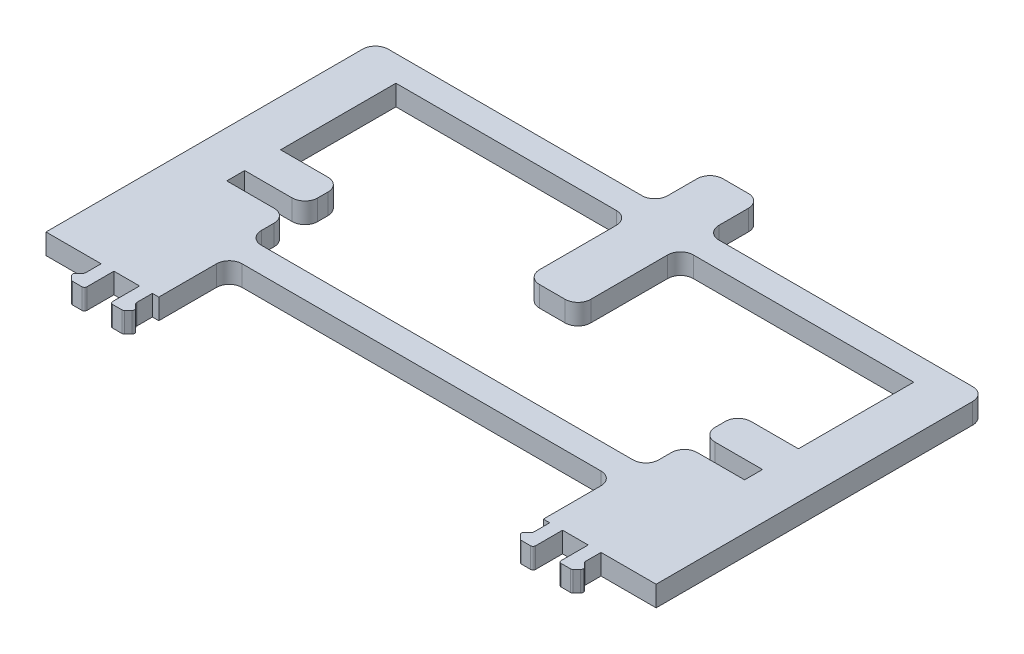
SolidWorks part; units mm, degrees
ref_plane "Front Plane" through (0, 0, 0) normal (0, 0, 1) x (1, 0, 0)
ref_plane "Top Plane" through (0, 0, 0) normal (0, 1, 0) x (1, 0, 0)
ref_plane "Right Plane" through (0, 0, 0) normal (1, 0, 0) x (0, 0, -1)
sketch "Sketch1" plane through (0, 0, 0) normal (0, 1, 0) x (1, 0, 0)
  line L0 (-68.9296, 0) -> (-64.6296, 0)
  line L1 (-60.1296, 0) -> (-60.1296, 5.5)
  line L2 (-65.3296, 23.7) -> (-47.1296, 23.7)
  line L3 (-65.3296, 10.5) -> (-65.3296, 11.9)
  line L4 (-65.3296, 11.9) -> (-60.6296, 11.9)
  line L5 (-64.6296, 0) -> (-64.6296, -1.3)
  line L6 (-60.6296, -2.3) -> (-61.6296, -2.3)
  line L7 (-60.6296, 7.5) -> (-45.1296, 7.5)
  line L8 (-47.1296, 23.7) -> (-47.1296, 15.7)
  line L9 (-47.1296, 15.7) -> (-45.1296, 15.7)
  line L10 (-68.9296, 25.7) -> (-47.1296, 25.7)
  line L11 (-63.6296, 0) -> (-61.6296, 0)
  line L12 (-68.9296, 0) -> (-68.9296, 20)
  line L13 (-47.1296, 30) -> (-45.1296, 30)
  line L14 (-45.1296, 30) -> (-45.1296, 0) construction
  line L16 (-63.6296, -2.3) -> (-63.6296, 0)
  line L17 (-60.6296, 14.7) -> (-65.3296, 14.7)
  line L18 (-61.6296, 0) -> (-61.6296, -2.3)
  line L19 (-47.1296, 25.7) -> (-47.1296, 30)
  line L20 (-64.6296, -1.3) -> (-65.1296, -1.8)
  line L21 (-65.1296, -1.8) -> (-64.6296, -2.3)
  line L22 (-65.3296, 14.7) -> (-65.3296, 23.7)
  line L23 (-60.6296, 0) -> (-60.6296, -1.3)
  line L24 (-60.6296, -1.3) -> (-60.1296, -1.8)
  line L25 (-60.1296, -1.8) -> (-60.6296, -2.3)
  line L26 (-45.1296, 15.7) -> (-45.1296, 30)
  line L27 (-65.3296, 10.5) -> (-60.6296, 10.5)
  line L29 (-60.6296, 14.7) -> (-60.6296, 11.9)
  line L31 (-45.1296, 5.5) -> (-60.1296, 5.5)
  line L32 (-60.6296, 0) -> (-60.1296, 0)
  line L33 (-60.6296, 7.5) -> (-60.6296, 10.5)
  line L35 (-64.6296, -2.3) -> (-63.6296, -2.3)
  line L44 (-45.1296, 7.5) -> (-45.1296, 5.5)
  line L61 (-68.9296, 20) -> (-68.9296, 25.7)
  point P54 (-60.6296, -1.3)
  point P57 (-60.1296, -1.8)
  point P74 (-61.6296, 0)
  point P77 (-63.6296, 0)
  point P86 (-64.6296, -2.3)
  point P89 (-65.1296, -1.8)
  point P92 (-64.6296, -1.3)
  dimension "D13" = 1
  dimension "D2" = 2
  dimension "D4" = 1.8
  dimension "D5" = 15.5
  dimension "D6" = 10.5
  dimension "D7" = 15
  dimension "D8" = 1.4
  dimension "D9" = 23.8
  dimension "D10" = 20.2
  dimension "D11" = 2
  dimension "D12" = 2.8
  dimension "D14" = 9
  dimension "D15" = 30
  dimension "D18" = 3
  dimension "D31" = 1
  dimension "D34" = 1
  dimension "D35" = 4
  dimension "D36" = 0.5
  dimension "D37" = 0.5
  dimension "D40" = 0.5
  dimension "D41" = 0.5
  dimension "D48" = 2
other "AlignGroup1"
extrude "Boss-Extrude1" add sketch "Sketch1" along normal blind 1.6
mirror "Mirror1" about plane through (-45.1296, 1.6, -15.7) normal (-1, 0, 0) of "Boss-Extrude1"
fillet "Fillet1" radius 1 10 edges at (-68.9296, 0.8, -25.7) (-21.3296, 0.8, -25.7) (-47.1296, 0.8, -30) (-43.1296, 0.8, -30) (-43.1296, 0.8, -25.7) (-47.1296, 0.8, -25.7) (-47.1296, 0.8, -23.7) (-43.1296, 0.8, -23.7) (-43.1296, 0.8, -15.7) (-47.1296, 0.8, -15.7)
fillet "Fillet2" radius 1 10 edges at (-29.6296, 0.8, -11.9) (-29.6296, 0.8, -14.7) (-30.1296, 0.8, -5.5) (-29.6296, 0.8, -7.5) (-60.1296, 0.8, -5.5) (-60.6296, 0.8, -7.5) (-60.6296, 0.8, -14.7) (-60.6296, 0.8, -11.9) (-60.6296, 0.8, -10.5) (-29.6296, 0.8, -10.5)
fillet "Fillet3" radius 0.2 16 edges at (-29.6296, 0.8, 1.3) (-29.6296, 0.8, 2.3) (-30.1296, 0.8, 1.8) (-26.6296, 0.8, 2.3) (-28.6296, 0.8, 2.3) (-25.6296, 0.8, 2.3) (-25.1296, 0.8, 1.8) (-25.6296, 0.8, 1.3) (-60.6296, 0.8, 1.3) (-61.6296, 0.8, 2.3) (-60.1296, 0.8, 1.8) (-60.6296, 0.8, 2.3) (-63.6296, 0.8, 2.3) (-64.6296, 0.8, 2.3) (-64.6296, 0.8, 1.3) (-65.1296, 0.8, 1.8)
